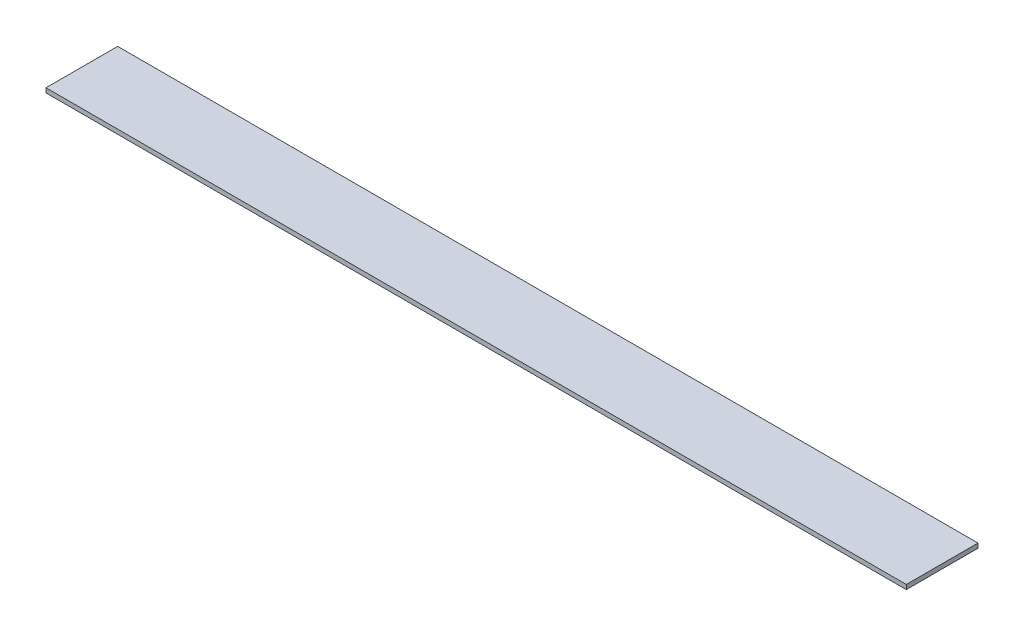
SolidWorks part; units mm, degrees
material "Nylon 101"
ref_plane "Front Plane" through (0, 0, 0) normal (0, 0, 1) x (1, 0, 0)
ref_plane "Top Plane" through (0, 0, 0) normal (0, 1, 0) x (1, 0, 0)
ref_plane "Right Plane" through (0, 0, 0) normal (1, 0, 0) x (0, 0, -1)
sketch "Sketch1" plane through (0, 0, 0) normal (0, 1, 0) x (1, 0, 0)
  line L1 (0, 0) -> (304.8, 0)
  line L2 (0, 0) -> (0, 25.4)
  line L3 (0, 25.4) -> (304.8, 25.4)
  line L4 (304.8, 0) -> (304.8, 25.4)
  dimension "D1" = 25.4
  dimension "D2" = 304.8
extrude "Boss-Extrude1" add sketch "Sketch1" along normal blind 1.5875
